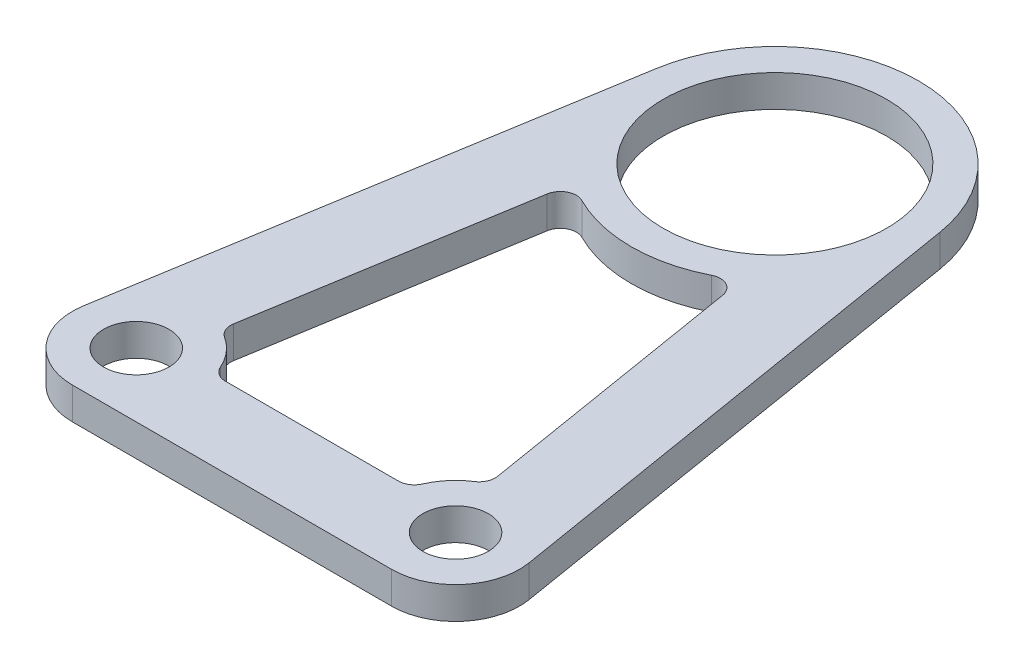
SolidWorks part; units mm, degrees
material "AISI 304"
ref_plane "Front Plane" through (0, 0, 0) normal (0, 0, 1) x (1, 0, 0)
ref_plane "Top Plane" through (0, 0, 0) normal (0, 1, 0) x (1, 0, 0)
ref_plane "Right Plane" through (0, 0, 0) normal (1, 0, 0) x (0, 0, -1)
sketch "Sketch1" plane through (0, 0, 0) normal (0, 1, 0) x (1, 0, 0)
  line L0 (0, 0) -> (0, -30) construction
  line L1 (42.4655, -30) -> (-42.4655, -30) construction
  line L2 (-8.8807, 1.4602) -> (-13.947, -29.351)
  line L3 (-10, -34) -> (10, -34)
  line L4 (8.8807, 1.4602) -> (13.947, -29.351)
  line L5 (-5.4948, -8.764) -> (-8.2697, -25.6404)
  line L6 (-5.4174, -29) -> (5.4174, -29)
  line L7 (5.4948, -8.764) -> (8.2697, -25.6404)
  line L8 (-3.947, 0.649) -> (-9.0133, -30.1622) construction
  line L10 (-10, -29) -> (10, -29) construction
  circle A0 centre (0, 0) radius 7
  arc A1 (-4.0572, -8.0336) -> (4.0572, -8.0336) centre (0, 0) ccw
  arc A2 (-6.3339, -28.4) -> (-7.8264, -26.6421) centre (-10, -30) ccw
  circle A3 centre (-10, -30) radius 2.05
  arc A4 (6.3339, -28.4) -> (7.8264, -26.6421) centre (10, -30) cw
  circle A5 centre (10, -30) radius 2.05
  arc A6 (-13.947, -29.351) -> (-10, -34) centre (-10, -30) ccw
  arc A7 (13.947, -29.351) -> (10, -34) centre (10, -30) cw
  arc A8 (8.8807, 1.4602) -> (-8.8807, 1.4602) centre (0, 0) ccw
  arc A9 (-8.2697, -25.6404) -> (-7.8264, -26.6421) centre (-7.283, -25.8026) ccw
  arc A10 (-5.4174, -29) -> (-6.3339, -28.4) centre (-5.4174, -28) cw
  arc A11 (5.4174, -29) -> (6.3339, -28.4) centre (5.4174, -28) ccw
  arc A12 (8.2697, -25.6404) -> (7.8264, -26.6421) centre (7.283, -25.8026) cw
  arc A13 (5.4948, -8.764) -> (4.0572, -8.0336) centre (4.508, -8.9262) ccw
  arc A14 (-5.4948, -8.764) -> (-4.0572, -8.0336) centre (-4.508, -8.9262) cw
  point P11 (-8.3849, -26.3406)
  point P35 (8.3849, -26.3406)
  point P38 (5.2551, -7.3064)
  point P41 (-5.2551, -7.3064)
  dimension "D1" = 14
  dimension "D2" = 18
  dimension "D4" = 8
  dimension "D5" = 4.1
  dimension "D9" = 1
  dimension "D3" = 30
  dimension "D6" = 10
  dimension "D7" = 5
  dimension "D8" = 5
extrude "Boss-Extrude1" add sketch "Sketch1" along normal blind 2
